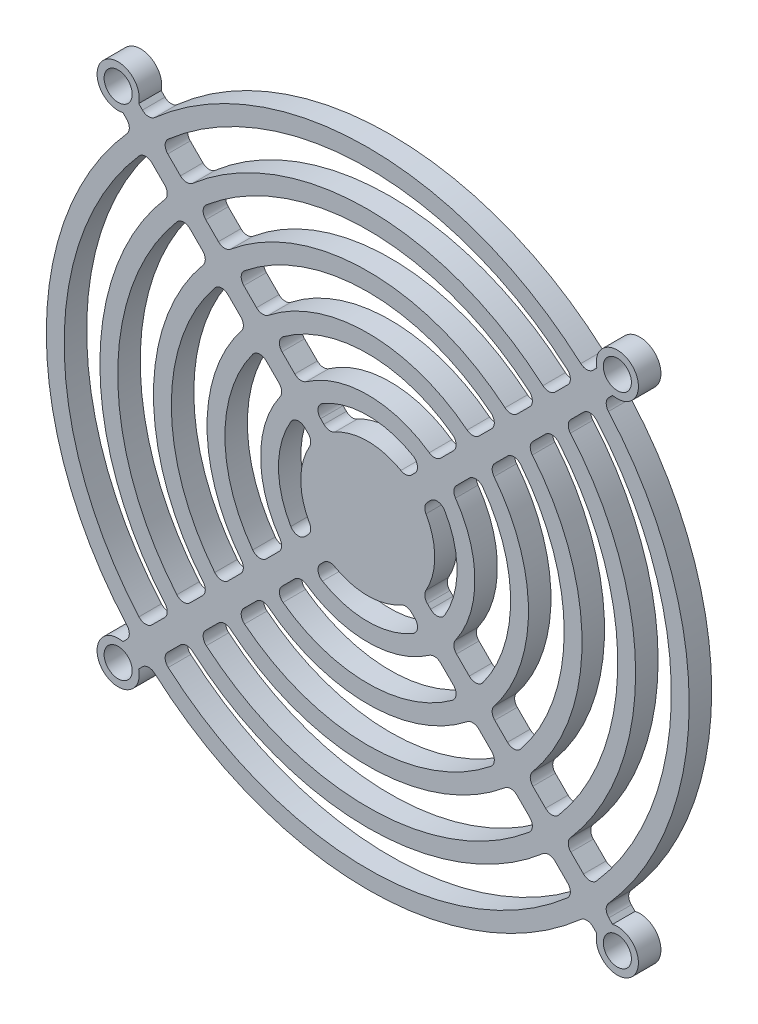
SolidWorks part; units mm, degrees
ref_plane "Front Plane" through (0, 0, 0) normal (0, 0, 1) x (1, 0, 0)
ref_plane "Top Plane" through (0, 0, 0) normal (0, 1, 0) x (1, 0, 0)
ref_plane "Right Plane" through (0, 0, 0) normal (1, 0, 0) x (0, 0, -1)
sketch "Sketch1" plane through (0, 0, 0) normal (0, 0, 1) x (1, 0, 0)
  line L0 (73.0094, 0) -> (-73.0094, 0) construction
  line L1 (0, -63.7995) -> (0, 63.7995) construction
  line L2 (-32.5775, 34.8226) -> (-32.0429, 34.288)
  line L3 (-34.8226, 32.5775) -> (-34.288, 32.0429)
  line L4 (-35.7623, 33.5173) -> (-33.5173, 35.7623) construction
  line L5 (-34.6398, 34.6398) -> (-35.5, 35.5) construction
  line L6 (-34.6398, 34.6398) -> (0, 0) construction
  line L7 (-8.9481, 6.7031) -> (-8.4835, 6.2384)
  line L8 (-6.7031, 8.9481) -> (-6.2384, 8.4835)
  line L9 (-14.4405, 12.1954) -> (-12.6207, 10.3756)
  line L10 (-12.1954, 14.4405) -> (-10.3756, 12.6207)
  line L11 (-19.8725, 17.6274) -> (-18.065, 15.8199)
  line L12 (-17.6274, 19.8725) -> (-15.8199, 18.065)
  line L13 (-25.2849, 23.0398) -> (-23.4821, 21.237)
  line L14 (-23.0398, 25.2849) -> (-21.237, 23.4821)
  line L15 (-28.4434, 30.6884) -> (-26.6428, 28.8879)
  line L16 (-30.6884, 28.4434) -> (-28.8879, 26.6428)
  line L17 (-35.7623, 33.5173) -> (-34.8226, 32.5775) construction
  line L18 (-33.5173, 35.7623) -> (-32.5775, 34.8226) construction
  line L19 (33.5173, 35.7623) -> (32.5775, 34.8226) construction
  line L20 (35.7623, 33.5173) -> (34.8226, 32.5775) construction
  line L21 (34.6398, 34.6398) -> (0, 0) construction
  line L22 (34.6398, 34.6398) -> (35.5, 35.5) construction
  line L23 (35.7623, 33.5173) -> (33.5173, 35.7623) construction
  line L24 (30.6884, 28.4434) -> (28.8879, 26.6428)
  line L25 (28.4434, 30.6884) -> (26.6428, 28.8879)
  line L26 (23.0398, 25.2849) -> (21.237, 23.4821)
  line L27 (25.2849, 23.0398) -> (23.4821, 21.237)
  line L28 (17.6274, 19.8725) -> (15.8199, 18.065)
  line L29 (19.8725, 17.6274) -> (18.065, 15.8199)
  line L30 (12.1954, 14.4405) -> (10.3756, 12.6207)
  line L31 (14.4405, 12.1954) -> (12.6207, 10.3756)
  line L32 (6.7031, 8.9481) -> (6.2384, 8.4835)
  line L33 (8.9481, 6.7031) -> (8.4835, 6.2384)
  line L34 (34.8226, 32.5775) -> (34.288, 32.0429)
  line L35 (32.5775, 34.8226) -> (32.0429, 34.288)
  line L36 (35.7623, -33.5173) -> (33.5173, -35.7623) construction
  line L37 (34.6398, -34.6398) -> (35.5, -35.5) construction
  line L38 (34.6398, -34.6398) -> (0, 0) construction
  line L39 (35.7623, -33.5173) -> (34.8226, -32.5775) construction
  line L40 (33.5173, -35.7623) -> (32.5775, -34.8226) construction
  line L41 (-33.5173, -35.7623) -> (-32.5775, -34.8226) construction
  line L42 (-35.7623, -33.5173) -> (-34.8226, -32.5775) construction
  line L43 (-34.6398, -34.6398) -> (0, 0) construction
  line L44 (-34.6398, -34.6398) -> (-35.5, -35.5) construction
  line L45 (-35.7623, -33.5173) -> (-33.5173, -35.7623) construction
  line L46 (32.5775, -34.8226) -> (32.0429, -34.288)
  line L47 (34.8226, -32.5775) -> (34.288, -32.0429)
  line L48 (8.9481, -6.7031) -> (8.4835, -6.2384)
  line L49 (6.7031, -8.9481) -> (6.2384, -8.4835)
  line L50 (14.4405, -12.1954) -> (12.6207, -10.3756)
  line L51 (12.1954, -14.4405) -> (10.3756, -12.6207)
  line L52 (19.8725, -17.6274) -> (18.065, -15.8199)
  line L53 (17.6274, -19.8725) -> (15.8199, -18.065)
  line L54 (25.2849, -23.0398) -> (23.4821, -21.237)
  line L55 (23.0398, -25.2849) -> (21.237, -23.4821)
  line L56 (28.4434, -30.6884) -> (26.6428, -28.8879)
  line L57 (30.6884, -28.4434) -> (28.8879, -26.6428)
  line L58 (-30.6884, -28.4434) -> (-28.8879, -26.6428)
  line L59 (-28.4434, -30.6884) -> (-26.6428, -28.8879)
  line L60 (-23.0398, -25.2849) -> (-21.237, -23.4821)
  line L61 (-25.2849, -23.0398) -> (-23.4821, -21.237)
  line L62 (-17.6274, -19.8725) -> (-15.8199, -18.065)
  line L63 (-19.8725, -17.6274) -> (-18.065, -15.8199)
  line L64 (-12.1954, -14.4405) -> (-10.3756, -12.6207)
  line L65 (-14.4405, -12.1954) -> (-12.6207, -10.3756)
  line L66 (-6.7031, -8.9481) -> (-6.2384, -8.4835)
  line L67 (-8.9481, -6.7031) -> (-8.4835, -6.2384)
  line L68 (-34.8226, -32.5775) -> (-34.288, -32.0429)
  line L69 (-32.5775, -34.8226) -> (-32.0429, -34.288)
  arc A0 (-33.5173, 35.7623) -> (-35.7623, 33.5173) centre (-35.5, 35.5) ccw construction
  arc A1 (-8.2778, 4.7121) -> (-8.2778, -4.7121) centre (0, 0) ccw
  arc A2 (6.45, 10.9402) -> (-6.45, 10.9402) centre (0, 0) ccw
  arc A3 (8.7485, 12.4788) -> (-8.7485, 12.4788) centre (0, 0) ccw
  arc A4 (12.0506, 16.3611) -> (-12.0506, 16.3611) centre (0, 0) ccw
  arc A5 (14.1365, 17.9649) -> (-14.1365, 17.9649) centre (0, 0) ccw
  arc A6 (17.5261, 21.7596) -> (-17.5261, 21.7596) centre (0, 0) ccw
  arc A7 (19.5254, 23.4049) -> (-19.5254, 23.4049) centre (0, 0) ccw
  arc A8 (22.9619, 27.1527) -> (-22.9619, 27.1527) centre (0, 0) ccw
  arc A9 (24.9143, 28.8251) -> (-24.9143, 28.8251) centre (0, 0) ccw
  arc A10 (28.38, 32.5436) -> (-28.38, 32.5436) centre (0, 0) ccw
  arc A11 (30.3031, 34.235) -> (-30.3031, 34.235) centre (0, 0) ccw
  arc A12 (-34.235, 30.3031) -> (-34.235, -30.3031) centre (0, 0) ccw
  arc A13 (-32.5436, 28.38) -> (-32.5436, -28.38) centre (0, 0) ccw
  arc A14 (-28.8251, 24.9143) -> (-28.8251, -24.9143) centre (0, 0) ccw
  arc A15 (-27.1527, 22.9619) -> (-27.1527, -22.9619) centre (0, 0) ccw
  arc A16 (-23.4049, 19.5254) -> (-23.4049, -19.5254) centre (0, 0) ccw
  arc A17 (-21.7596, 17.5261) -> (-21.7596, -17.5261) centre (0, 0) ccw
  arc A18 (-17.9649, 14.1365) -> (-17.9649, -14.1365) centre (0, 0) ccw
  arc A19 (-12.4788, 8.7485) -> (-12.4788, -8.7485) centre (0, 0) ccw
  arc A20 (-10.9402, 6.45) -> (-10.9402, -6.45) centre (0, 0) ccw
  arc A21 (-16.3611, 12.0506) -> (-16.3611, -12.0506) centre (0, 0) ccw
  arc A22 (4.7121, 8.2778) -> (-4.7121, 8.2778) centre (0, 0) ccw
  arc A23 (-32.5775, 34.8226) -> (-34.8226, 32.5775) centre (-35.5, 35.5) ccw
  circle A24 centre (-35.5, 35.5) radius 2
  arc A25 (-6.2384, 8.4835) -> (-4.7121, 8.2778) centre (-5.3404, 9.3815) ccw
  arc A26 (-8.4835, 6.2384) -> (-8.2778, 4.7121) centre (-9.3815, 5.3404) cw
  arc A27 (-8.9481, 6.7031) -> (-10.9402, 6.45) centre (-9.8461, 5.805) ccw
  arc A28 (-6.7031, 8.9481) -> (-6.45, 10.9402) centre (-5.805, 9.8461) cw
  arc A29 (-8.7485, 12.4788) -> (-10.3756, 12.6207) centre (-9.4776, 13.5187) cw
  arc A30 (-12.4788, 8.7485) -> (-12.6207, 10.3756) centre (-13.5187, 9.4776) ccw
  arc A31 (-14.4405, 12.1954) -> (-16.3611, 12.0506) centre (-15.3385, 11.2974) ccw
  arc A32 (-12.1954, 14.4405) -> (-12.0506, 16.3611) centre (-11.2974, 15.3385) cw
  arc A33 (-14.1365, 17.9649) -> (-15.8199, 18.065) centre (-14.9219, 18.963) cw
  arc A34 (-17.9649, 14.1365) -> (-18.065, 15.8199) centre (-18.963, 14.9219) ccw
  arc A35 (-17.6274, 19.8725) -> (-17.5261, 21.7596) centre (-16.7294, 20.7705) cw
  arc A36 (-19.8725, 17.6274) -> (-21.7596, 17.5261) centre (-20.7705, 16.7294) ccw
  arc A37 (-19.5254, 23.4049) -> (-21.237, 23.4821) centre (-20.339, 24.3801) cw
  arc A38 (-23.4049, 19.5254) -> (-23.4821, 21.237) centre (-24.3801, 20.339) ccw
  arc A39 (-23.0398, 25.2849) -> (-22.9619, 27.1527) centre (-22.1418, 26.1829) cw
  arc A40 (-25.2849, 23.0398) -> (-27.1527, 22.9619) centre (-26.1829, 22.1418) ccw
  arc A41 (-24.9143, 28.8251) -> (-26.6428, 28.8879) centre (-25.7448, 29.7859) cw
  arc A42 (-28.8251, 24.9143) -> (-28.8879, 26.6428) centre (-29.7859, 25.7448) ccw
  arc A43 (-28.4434, 30.6884) -> (-28.38, 32.5436) centre (-27.5453, 31.5864) cw
  arc A44 (-30.6884, 28.4434) -> (-32.5436, 28.38) centre (-31.5864, 27.5453) ccw
  arc A45 (-32.0429, 34.288) -> (-30.3031, 34.235) centre (-31.1449, 35.186) ccw
  arc A46 (-34.288, 32.0429) -> (-34.235, 30.3031) centre (-35.186, 31.1449) cw
  arc A47 (33.5173, 35.7623) -> (35.7623, 33.5173) centre (35.5, 35.5) cw construction
  arc A48 (34.288, 32.0429) -> (34.235, 30.3031) centre (35.186, 31.1449) ccw
  arc A49 (32.0429, 34.288) -> (30.3031, 34.235) centre (31.1449, 35.186) cw
  arc A50 (30.6884, 28.4434) -> (32.5436, 28.38) centre (31.5864, 27.5453) cw
  arc A51 (28.4434, 30.6884) -> (28.38, 32.5436) centre (27.5453, 31.5864) ccw
  arc A52 (28.8251, 24.9143) -> (28.8879, 26.6428) centre (29.7859, 25.7448) cw
  arc A53 (24.9143, 28.8251) -> (26.6428, 28.8879) centre (25.7448, 29.7859) ccw
  arc A54 (25.2849, 23.0398) -> (27.1527, 22.9619) centre (26.1829, 22.1418) cw
  arc A55 (23.0398, 25.2849) -> (22.9619, 27.1527) centre (22.1418, 26.1829) ccw
  arc A56 (23.4049, 19.5254) -> (23.4821, 21.237) centre (24.3801, 20.339) cw
  arc A57 (19.5254, 23.4049) -> (21.237, 23.4821) centre (20.339, 24.3801) ccw
  arc A58 (19.8725, 17.6274) -> (21.7596, 17.5261) centre (20.7705, 16.7294) cw
  arc A59 (17.6274, 19.8725) -> (17.5261, 21.7596) centre (16.7294, 20.7705) ccw
  arc A60 (17.9649, 14.1365) -> (18.065, 15.8199) centre (18.963, 14.9219) cw
  arc A61 (14.1365, 17.9649) -> (15.8199, 18.065) centre (14.9219, 18.963) ccw
  arc A62 (12.1954, 14.4405) -> (12.0506, 16.3611) centre (11.2974, 15.3385) ccw
  arc A63 (14.4405, 12.1954) -> (16.3611, 12.0506) centre (15.3385, 11.2974) cw
  arc A64 (12.4788, 8.7485) -> (12.6207, 10.3756) centre (13.5187, 9.4776) cw
  arc A65 (8.7485, 12.4788) -> (10.3756, 12.6207) centre (9.4776, 13.5187) ccw
  arc A66 (6.7031, 8.9481) -> (6.45, 10.9402) centre (5.805, 9.8461) ccw
  arc A67 (8.9481, 6.7031) -> (10.9402, 6.45) centre (9.8461, 5.805) cw
  arc A68 (8.4835, 6.2384) -> (8.2778, 4.7121) centre (9.3815, 5.3404) ccw
  arc A69 (6.2384, 8.4835) -> (4.7121, 8.2778) centre (5.3404, 9.3815) cw
  circle A70 centre (35.5, 35.5) radius 2
  arc A71 (32.5775, 34.8226) -> (34.8226, 32.5775) centre (35.5, 35.5) cw
  arc A72 (16.3611, 12.0506) -> (16.3611, -12.0506) centre (0, 0) cw
  arc A73 (10.9402, 6.45) -> (10.9402, -6.45) centre (0, 0) cw
  arc A74 (12.4788, 8.7485) -> (12.4788, -8.7485) centre (0, 0) cw
  arc A75 (17.9649, 14.1365) -> (17.9649, -14.1365) centre (0, 0) cw
  arc A76 (21.7596, 17.5261) -> (21.7596, -17.5261) centre (0, 0) cw
  arc A77 (23.4049, 19.5254) -> (23.4049, -19.5254) centre (0, 0) cw
  arc A78 (27.1527, 22.9619) -> (27.1527, -22.9619) centre (0, 0) cw
  arc A79 (28.8251, 24.9143) -> (28.8251, -24.9143) centre (0, 0) cw
  arc A80 (32.5436, 28.38) -> (32.5436, -28.38) centre (0, 0) cw
  arc A81 (34.235, 30.3031) -> (34.235, -30.3031) centre (0, 0) cw
  arc A82 (8.2778, 4.7121) -> (8.2778, -4.7121) centre (0, 0) cw
  arc A83 (33.5173, -35.7623) -> (35.7623, -33.5173) centre (35.5, -35.5) ccw construction
  arc A84 (-33.5173, -35.7623) -> (-35.7623, -33.5173) centre (-35.5, -35.5) cw construction
  arc A85 (32.5775, -34.8226) -> (34.8226, -32.5775) centre (35.5, -35.5) ccw
  circle A86 centre (35.5, -35.5) radius 2
  arc A87 (6.2384, -8.4835) -> (4.7121, -8.2778) centre (5.3404, -9.3815) ccw
  arc A88 (8.4835, -6.2384) -> (8.2778, -4.7121) centre (9.3815, -5.3404) cw
  arc A89 (8.9481, -6.7031) -> (10.9402, -6.45) centre (9.8461, -5.805) ccw
  arc A90 (6.7031, -8.9481) -> (6.45, -10.9402) centre (5.805, -9.8461) cw
  arc A91 (8.7485, -12.4788) -> (10.3756, -12.6207) centre (9.4776, -13.5187) cw
  arc A92 (12.4788, -8.7485) -> (12.6207, -10.3756) centre (13.5187, -9.4776) ccw
  arc A93 (14.4405, -12.1954) -> (16.3611, -12.0506) centre (15.3385, -11.2974) ccw
  arc A94 (12.1954, -14.4405) -> (12.0506, -16.3611) centre (11.2974, -15.3385) cw
  arc A95 (14.1365, -17.9649) -> (15.8199, -18.065) centre (14.9219, -18.963) cw
  arc A96 (17.9649, -14.1365) -> (18.065, -15.8199) centre (18.963, -14.9219) ccw
  arc A97 (17.6274, -19.8725) -> (17.5261, -21.7596) centre (16.7294, -20.7705) cw
  arc A98 (19.8725, -17.6274) -> (21.7596, -17.5261) centre (20.7705, -16.7294) ccw
  arc A99 (19.5254, -23.4049) -> (21.237, -23.4821) centre (20.339, -24.3801) cw
  arc A100 (23.4049, -19.5254) -> (23.4821, -21.237) centre (24.3801, -20.339) ccw
  arc A101 (23.0398, -25.2849) -> (22.9619, -27.1527) centre (22.1418, -26.1829) cw
  arc A102 (25.2849, -23.0398) -> (27.1527, -22.9619) centre (26.1829, -22.1418) ccw
  arc A103 (24.9143, -28.8251) -> (26.6428, -28.8879) centre (25.7448, -29.7859) cw
  arc A104 (28.8251, -24.9143) -> (28.8879, -26.6428) centre (29.7859, -25.7448) ccw
  arc A105 (28.4434, -30.6884) -> (28.38, -32.5436) centre (27.5453, -31.5864) cw
  arc A106 (30.6884, -28.4434) -> (32.5436, -28.38) centre (31.5864, -27.5453) ccw
  arc A107 (32.0429, -34.288) -> (30.3031, -34.235) centre (31.1449, -35.186) ccw
  arc A108 (34.288, -32.0429) -> (34.235, -30.3031) centre (35.186, -31.1449) cw
  arc A109 (-34.288, -32.0429) -> (-34.235, -30.3031) centre (-35.186, -31.1449) ccw
  arc A110 (-32.0429, -34.288) -> (-30.3031, -34.235) centre (-31.1449, -35.186) cw
  arc A111 (-30.6884, -28.4434) -> (-32.5436, -28.38) centre (-31.5864, -27.5453) cw
  arc A112 (-28.4434, -30.6884) -> (-28.38, -32.5436) centre (-27.5453, -31.5864) ccw
  arc A113 (-28.8251, -24.9143) -> (-28.8879, -26.6428) centre (-29.7859, -25.7448) cw
  arc A114 (-24.9143, -28.8251) -> (-26.6428, -28.8879) centre (-25.7448, -29.7859) ccw
  arc A115 (-25.2849, -23.0398) -> (-27.1527, -22.9619) centre (-26.1829, -22.1418) cw
  arc A116 (-23.0398, -25.2849) -> (-22.9619, -27.1527) centre (-22.1418, -26.1829) ccw
  arc A117 (-23.4049, -19.5254) -> (-23.4821, -21.237) centre (-24.3801, -20.339) cw
  arc A118 (-19.5254, -23.4049) -> (-21.237, -23.4821) centre (-20.339, -24.3801) ccw
  arc A119 (-19.8725, -17.6274) -> (-21.7596, -17.5261) centre (-20.7705, -16.7294) cw
  arc A120 (-17.6274, -19.8725) -> (-17.5261, -21.7596) centre (-16.7294, -20.7705) ccw
  arc A121 (-17.9649, -14.1365) -> (-18.065, -15.8199) centre (-18.963, -14.9219) cw
  arc A122 (-14.1365, -17.9649) -> (-15.8199, -18.065) centre (-14.9219, -18.963) ccw
  arc A123 (-12.1954, -14.4405) -> (-12.0506, -16.3611) centre (-11.2974, -15.3385) ccw
  arc A124 (-14.4405, -12.1954) -> (-16.3611, -12.0506) centre (-15.3385, -11.2974) cw
  arc A125 (-12.4788, -8.7485) -> (-12.6207, -10.3756) centre (-13.5187, -9.4776) cw
  arc A126 (-8.7485, -12.4788) -> (-10.3756, -12.6207) centre (-9.4776, -13.5187) ccw
  arc A127 (-6.7031, -8.9481) -> (-6.45, -10.9402) centre (-5.805, -9.8461) ccw
  arc A128 (-8.9481, -6.7031) -> (-10.9402, -6.45) centre (-9.8461, -5.805) cw
  arc A129 (-8.4835, -6.2384) -> (-8.2778, -4.7121) centre (-9.3815, -5.3404) ccw
  arc A130 (-6.2384, -8.4835) -> (-4.7121, -8.2778) centre (-5.3404, -9.3815) cw
  circle A131 centre (-35.5, -35.5) radius 2
  arc A132 (-32.5775, -34.8226) -> (-34.8226, -32.5775) centre (-35.5, -35.5) cw
  arc A133 (4.7121, -8.2778) -> (-4.7121, -8.2778) centre (0, 0) cw
  arc A134 (30.3031, -34.235) -> (-30.3031, -34.235) centre (0, 0) cw
  arc A135 (28.38, -32.5436) -> (-28.38, -32.5436) centre (0, 0) cw
  arc A136 (24.9143, -28.8251) -> (-24.9143, -28.8251) centre (0, 0) cw
  arc A137 (22.9619, -27.1527) -> (-22.9619, -27.1527) centre (0, 0) cw
  arc A138 (19.5254, -23.4049) -> (-19.5254, -23.4049) centre (0, 0) cw
  arc A139 (17.5261, -21.7596) -> (-17.5261, -21.7596) centre (0, 0) cw
  arc A140 (14.1365, -17.9649) -> (-14.1365, -17.9649) centre (0, 0) cw
  arc A141 (12.0506, -16.3611) -> (-12.0506, -16.3611) centre (0, 0) cw
  arc A142 (8.7485, -12.4788) -> (-8.7485, -12.4788) centre (0, 0) cw
  arc A143 (6.45, -10.9402) -> (-6.45, -10.9402) centre (0, 0) cw
  point P5 (10.0324, -7.7873)
  point P8 (-33.432, -31.1869)
  point P10 (-31.6348, -29.3897)
  point P12 (-28.0399, -25.7948)
  point P15 (-26.2422, -23.9971)
  point P16 (-22.6459, -20.4008)
  point P17 (-20.8472, -18.6021)
  point P18 (-17.248, -15.0029)
  point P35 (-15.447, -13.202)
  point P37 (33.432, 31.1869)
  point P38 (31.6348, 29.3897)
  point P39 (28.0399, 25.7948)
  point P40 (26.2422, 23.9971)
  point P41 (22.6459, 20.4008)
  point P42 (20.8472, 18.6021)
  point P43 (17.248, 15.0029)
  point P45 (-11.8402, -9.5952)
  point P46 (15.447, 13.202)
  point P47 (11.8402, 9.5952)
  point P51 (-10.0324, -7.7873)
  point P61 (-10.0324, 7.7873)
  point P68 (-11.8402, 9.5952)
  point P71 (-15.447, 13.202)
  point P78 (-17.248, 15.0029)
  point P83 (-20.8472, 18.6021)
  point P88 (-22.6459, 20.4008)
  point P93 (-26.2422, 23.9971)
  point P98 (-28.0399, 25.7948)
  point P103 (-31.6348, 29.3897)
  point P108 (-33.432, 31.1869)
  point P192 (10.0324, 7.7873)
  point P329 (11.8402, -9.5952)
  point P330 (15.447, -13.202)
  point P331 (17.248, -15.0029)
  point P332 (20.8472, -18.6021)
  point P333 (22.6459, -20.4008)
  point P334 (26.2422, -23.9971)
  point P335 (28.0399, -25.7948)
  point P336 (31.6348, -29.3897)
  point P337 (33.432, -31.1869)
  dimension "D3" = 4
  dimension "D5" = 19.05
  dimension "D6" = 12.7
  dimension "D7" = 15.24
  dimension "D8" = 20.32
  dimension "D9" = 22.86
  dimension "D10" = 27.94
  dimension "D11" = 30.48
  dimension "D12" = 35.56
  dimension "D13" = 38.1
  dimension "D14" = 43.18
  dimension "D15" = 45.72
  dimension "D16" = 6
  dimension "D17" = 1.27
  dimension "D1" = 71
  dimension "D2" = 71
  dimension "D4" = 3.175
extrude "Boss-Extrude1" add sketch "Sketch1" along normal blind 3.2
